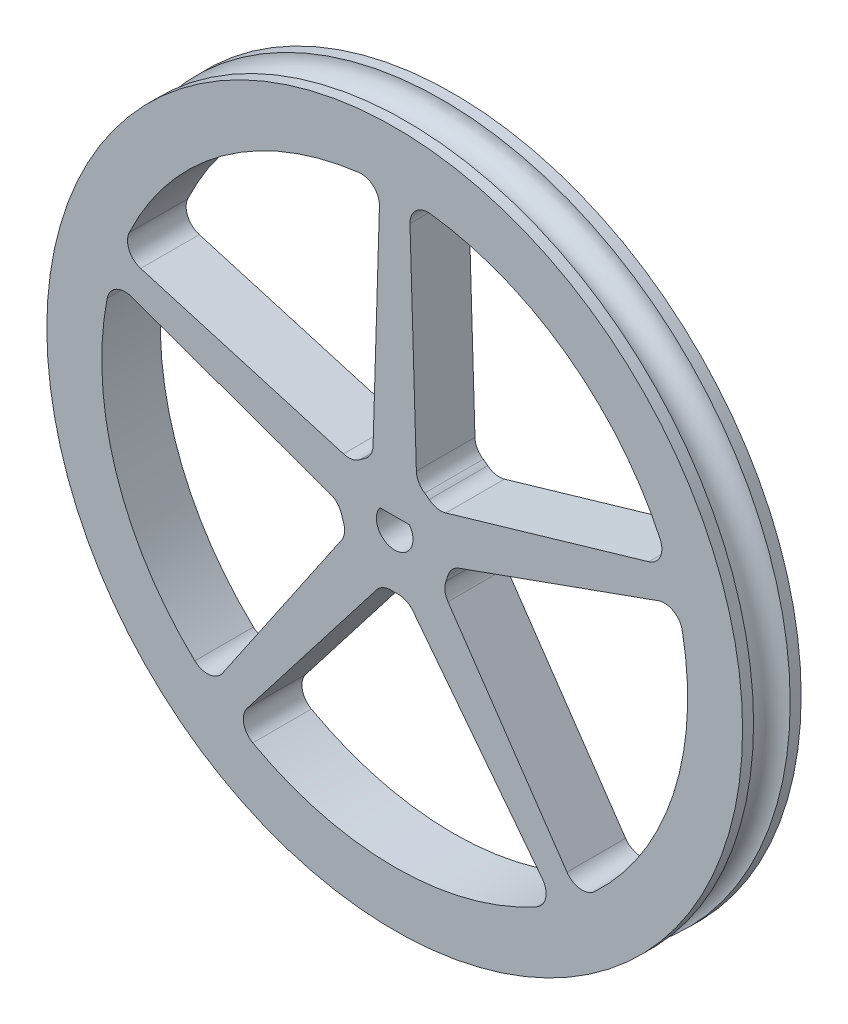
SolidWorks part; units mm, degrees
ref_plane "Front Plane" through (0, 0, 0) normal (0, 0, 1) x (1, 0, 0)
ref_plane "Top Plane" through (0, 0, 0) normal (0, 1, 0) x (1, 0, 0)
ref_plane "Right Plane" through (0, 0, 0) normal (1, 0, 0) x (0, 0, -1)
sketch "Sketch1" plane through (0, 0, 0) normal (0, 0, 1) x (1, 0, 0)
  line L0 (1.27, 0.9525) -> (-1.27, 0.9525)
  circle A0 centre (0, 0) radius 1.5875 construction
  arc A1 (1.27, 0.9525) -> (-1.27, 0.9525) centre (0, 0) cw
  circle A2 centre (0, 0) radius 30.1625
  point P6 (0, 1.5875)
  point P7 (0, -1.5875)
  dimension "D1" = 3.175
  dimension "D3" = 60.325
  dimension "D2" = 2.54
extrude "Boss-Extrude1" add sketch "Sketch1" along normal mid plane 5.08
sketch "Sketch2" plane through (0, 0, 0) normal (0, 1, 0) x (1, 0, 0)
  line L0 (0, 0) -> (0, 12.7709) construction
  line L1 (30.1625, -2.54) -> (30.1625, 2.54) construction
  circle A0 centre (30.1625, 0) radius 1.5875
  point P5 (0, 0)
  point P6 (30.1625, 0)
  dimension "D1" = 3.175
revolve "Cut-Revolve1" cut sketch "Sketch2" angle 360 about L0
sketch "Sketch4" plane through (0, 0, 2.54) normal (0, 0, 1) x (1, 0, 0)
  line L0 (-1.905, 4.3649) -> (-1.27, 25.3682)
  line L1 (1.27, 25.3682) -> (1.905, 4.3649)
  line L2 (0, 25.4) -> (0, 0) construction
  line L3 (24.5191, 6.6314) -> (4.7399, -0.4629)
  line L4 (3.5626, 3.1606) -> (23.7342, 9.0471)
  line L5 (13.8836, -21.2698) -> (1.0244, -4.651)
  line L6 (4.1068, -2.4116) -> (15.9385, -19.7768)
  line L7 (-15.9385, -19.7768) -> (-4.1068, -2.4116)
  line L8 (-1.0244, -4.651) -> (-13.8836, -21.2698)
  line L9 (-23.7342, 9.0471) -> (-3.5626, 3.1606)
  line L10 (-4.7399, -0.4629) -> (-24.5191, 6.6314)
  circle A0 centre (0, 0) radius 4.7625
  circle A1 centre (0, 0) radius 25.4
  circle A2 centre (0, 0) radius 30.1625 construction
  arc A3 (-1.27, 0.9525) -> (1.27, 0.9525) centre (0, 0) ccw construction
  point P14 (13.4463, -2.5728)
  point P15 (0, 0)
  point P33 (0, 0)
  dimension "D1" = 4.7625
  dimension "D2" = 3.175
  dimension "D3" = 3.81
  dimension "D4" = 2.54
  dimension "D5" = 5
extrude "Cut-Extrude1" cut sketch "Sketch4" against normal through all contours L0 A1 L9 A0 | L4 A1 L1 A0 | L6 A1 L3 A0 | L8 A1 L5 A0 | L10 A1 L7 A0
fillet "Fillet1" radius 1.5875 20 edges at (-3.5626, 3.1606, 0) (-23.7342, 9.0471, 0) (-1.27, 25.3682, 0) (-1.905, 4.3649, 0) (1.0244, -4.651, 0) (13.8836, -21.2698, 0) (-13.8836, -21.2698, 0) (-1.0244, -4.651, 0) (-4.1068, -2.4116, 0) (-15.9385, -19.7768, 0) (-24.5191, 6.6314, 0) (-4.7399, -0.4629, 0) (1.905, 4.3649, 0) (1.27, 25.3682, 0) (3.5626, 3.1606, 0) (4.7399, -0.4629, 0) (24.5191, 6.6314, 0) (15.9385, -19.7768, 0) (4.1068, -2.4116, 0) (23.7342, 9.0471, 0)
